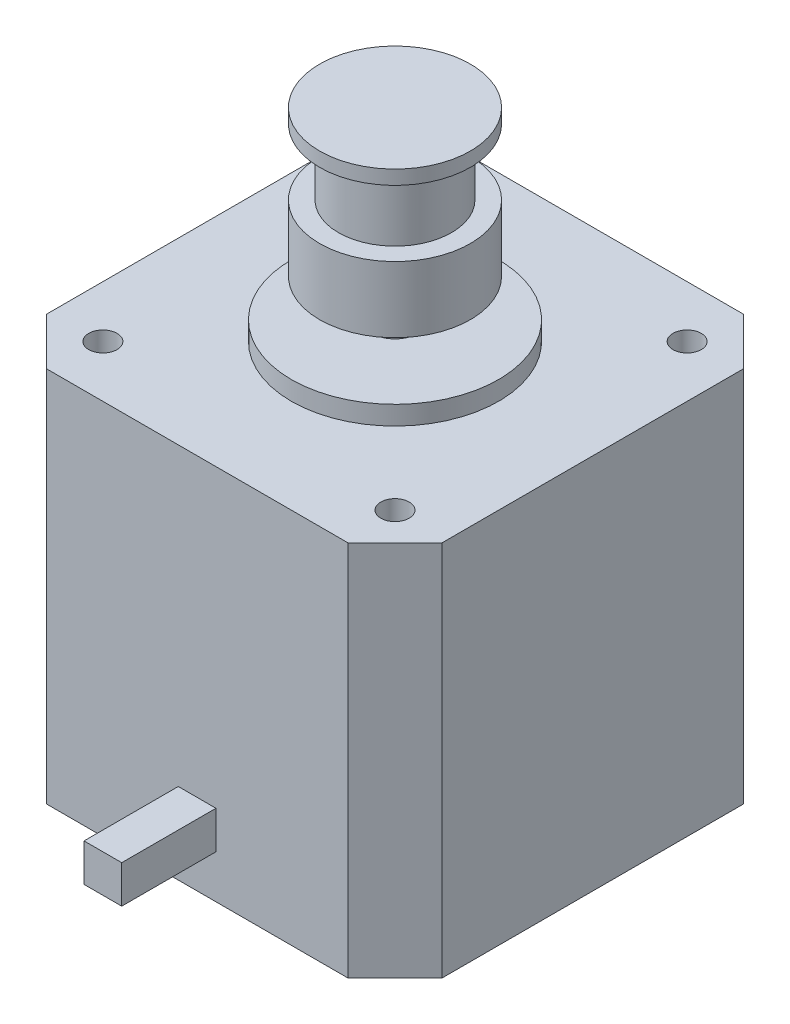
SolidWorks part; units mm, degrees
ref_plane "Front Plane" through (0, 0, 0) normal (0, 0, 1) x (1, 0, 0)
ref_plane "Top Plane" through (0, 0, 0) normal (0, 1, 0) x (1, 0, 0)
ref_plane "Right Plane" through (0, 0, 0) normal (1, 0, 0) x (0, 0, -1)
sketch "Sketch1" plane through (0, 0, 0) normal (0, 1, 0) x (1, 0, 0)
  line L1 (-21, -21) -> (21, -21)
  line L2 (-21, -21) -> (-21, 21)
  line L3 (-21, 21) -> (21, 21)
  line L4 (21, -21) -> (21, 21)
  line L5 (-21, -21) -> (21, 21) construction
  line L6 (-21, 21) -> (21, -21) construction
  point P0 (0, 0)
  dimension "D1" = 42
extrude "Boss-Extrude1" add sketch "Sketch1" along normal blind 40
sketch "Sketch2" plane through (0, 40, 0) normal (0, 1, 0) x (1, 0, 0)
  circle A0 centre (0, 0) radius 11
  dimension "D1" = 22
chamfer "Chamfer1" distance 5 angle 45 4 edges at (-21, 20, -21) (21, 20, -21) (-21, 20, 21) (21, 20, 21)
extrude "Boss-Extrude3" add sketch "Sketch2" along normal blind 2 contours A0
sketch "Sketch5" plane through (0, 42, 0) normal (0, 1, 0) x (1, 0, 0)
  circle A0 centre (0, 0) radius 2.5
  dimension "D1" = 5
extrude "Boss-Extrude4" add sketch "Sketch5" along normal blind 4
sketch "Sketch6" plane through (0, 46, 0) normal (0, 1, 0) x (1, 0, 0)
  circle A0 centre (0, 0) radius 8
  dimension "D1" = 16
extrude "Boss-Extrude5" add sketch "Sketch6" along normal blind 7
sketch "Sketch7" plane through (0, 53, 0) normal (0, 1, 0) x (1, 0, 0)
  circle A0 centre (0, 0) radius 6
  dimension "D1" = 12
extrude "Boss-Extrude6" add sketch "Sketch7" along normal blind 7
sketch "Sketch8" plane through (0, 60, 0) normal (0, 1, 0) x (1, 0, 0)
  circle A0 centre (0, 0) radius 8
  dimension "D1" = 16
extrude "Boss-Extrude7" add sketch "Sketch8" along normal blind 1.5
sketch "Sketch9" plane through (0, 40, 0) normal (0, 1, 0) x (1, 0, 0)
  line L1 (-15.5, -15.5) -> (15.5, -15.5) construction
  line L2 (-15.5, -15.5) -> (-15.5, 15.5) construction
  line L3 (-15.5, 15.5) -> (15.5, 15.5) construction
  line L4 (15.5, -15.5) -> (15.5, 15.5) construction
  line L5 (-15.5, -15.5) -> (15.5, 15.5) construction
  line L6 (-15.5, 15.5) -> (15.5, -15.5) construction
  circle A0 centre (-15.5, 15.5) radius 1.5
  circle A1 centre (15.5, 15.5) radius 1.5
  circle A2 centre (15.5, -15.5) radius 1.5
  circle A3 centre (-15.5, -15.5) radius 1.5
  point P0 (0, 0)
  dimension "D2" = 3
  dimension "D1" = 31
extrude "Cut-Extrude1" cut sketch "Sketch9" against normal blind 4.5
sketch "Sketch10" plane through (0, 0, 21) normal (0, 0, 1) x (1, 0, 0)
  line L1 (-2, 4.6) -> (2, 4.6)
  line L2 (-2, 4.6) -> (-2, 8.6)
  line L3 (-2, 8.6) -> (2, 8.6)
  line L4 (2, 4.6) -> (2, 8.6)
  line L5 (-2, 4.6) -> (2, 8.6) construction
  line L6 (-2, 8.6) -> (2, 4.6) construction
  point P0 (0, 6.6)
  point P5 (0, 0)
  dimension "D1" = 4
  dimension "D2" = 4.6
extrude "Boss-Extrude8" add sketch "Sketch10" along normal blind 10
